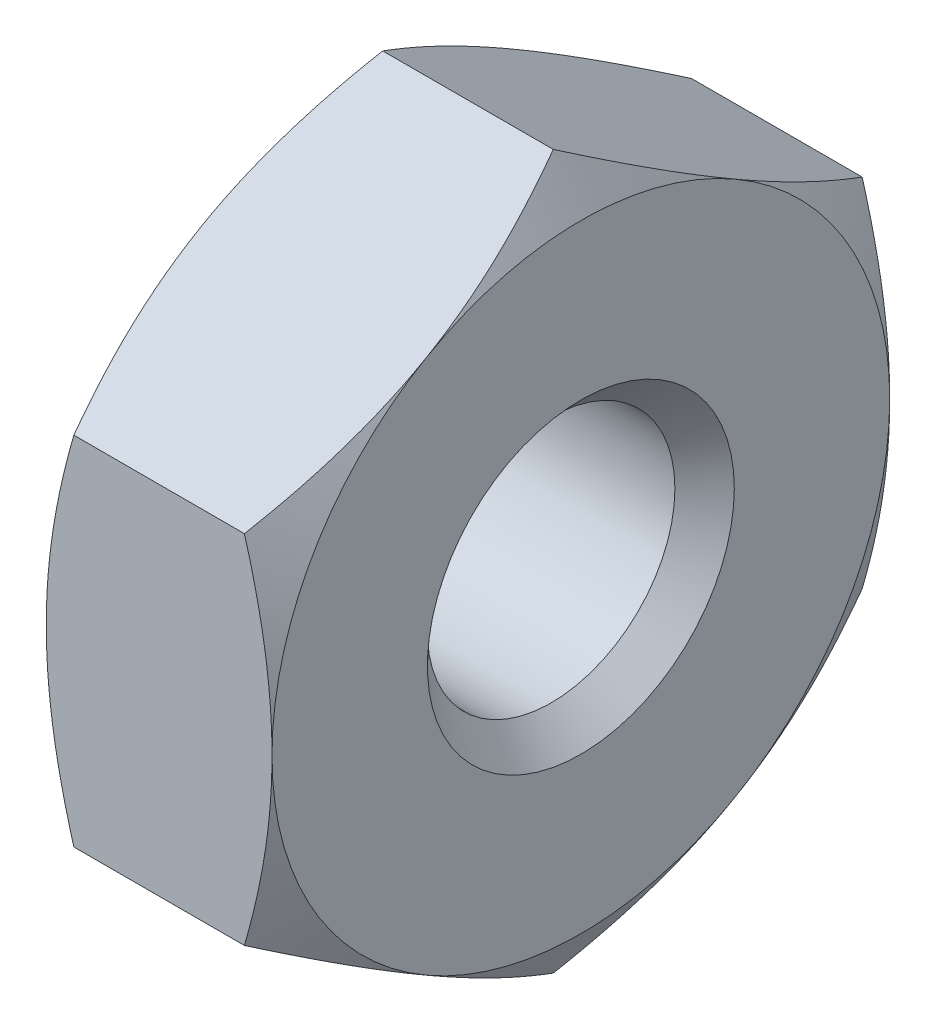
SolidWorks part; units mm, degrees
ref_plane "Front Plane" through (0, 0, 0) normal (0, 0, 1) x (1, 0, 0)
ref_plane "Top Plane" through (0, 0, 0) normal (0, 1, 0) x (1, 0, 0)
ref_plane "Right Plane" through (0, 0, 0) normal (1, 0, 0) x (0, 0, -1)
sketch "Sketch1" plane through (0, 0, 0) normal (1, 0, 0) x (0, 0, -1)
  line L1 (0, -4.5754) -> (3.9624, -2.2877)
  line L2 (3.9624, -2.2877) -> (3.9624, 2.2877)
  line L3 (3.9624, 2.2877) -> (0, 4.5754)
  line L4 (0, 4.5754) -> (-3.9624, 2.2877)
  line L5 (-3.9624, 2.2877) -> (-3.9624, -2.2877)
  line L6 (-3.9624, -2.2877) -> (0, -4.5754)
  circle A0 centre (0, 0) radius 1.5875
  circle A2 centre (0, 0) radius 3.9624 construction
  dimension "D1" = 3.175
extrude "Boss-Extrude2" add sketch "Sketch1" along normal blind 2.8956
sketch "Sketch2" plane through (0, 0, 0) normal (-1, 0, 0) x (0, 0, 1)
  circle A0 centre (0, 0) radius 3.9624
extrude "Cut-Extrude7" cut sketch "Sketch2" against normal through all draft 60 flip side to cut contours A0
ref_plane "Plane1" through (1.4478, 0, 0) normal (-1, 0, 0) x (0, 0, 1)
mirror "Mirror1" about plane through (1.4478, 0, 0) normal (-1, 0, 0) of "Cut-Extrude7"
chamfer "Chamfer1" distance 0.381 angle 45 2 edges at (2.8956, 0, -1.5875) (0, 0, -1.5875)
